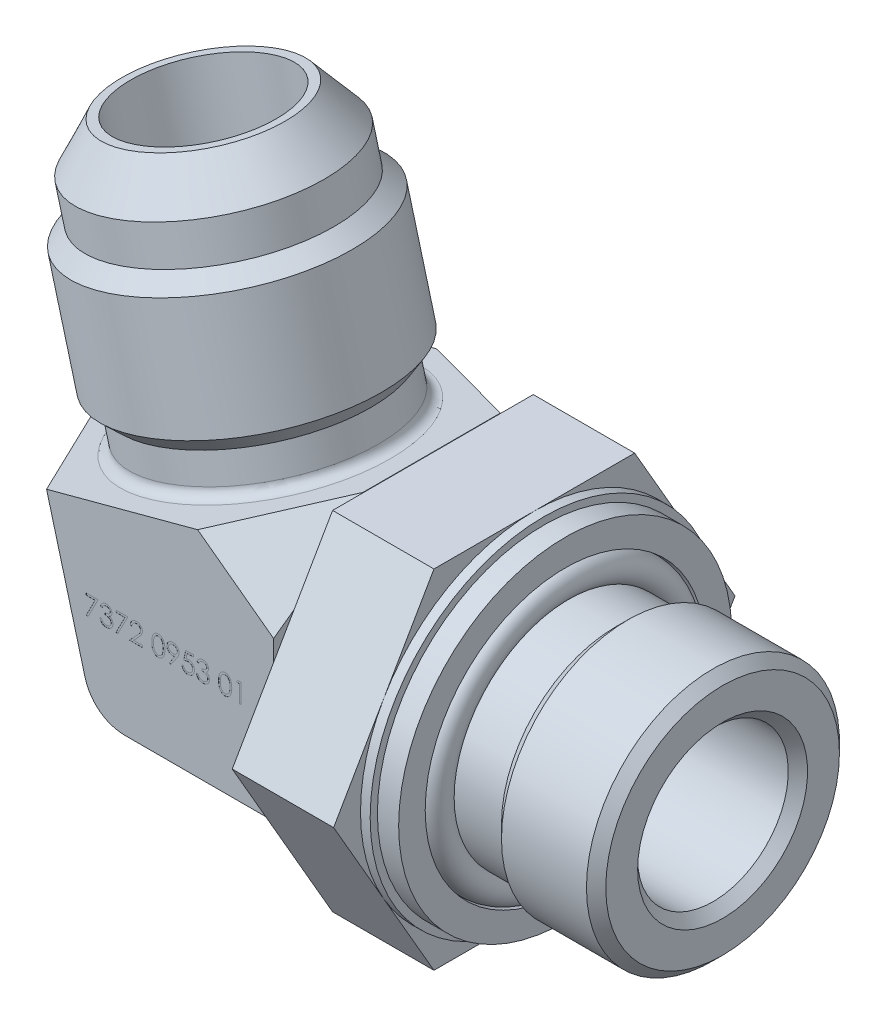
SolidWorks part; units mm, degrees
material "4140 H/T"
ref_plane "Front Plane" through (0, 0, 0) normal (0, 0, 1) x (1, 0, 0)
ref_plane "Top Plane" through (0, 0, 0) normal (0, 1, 0) x (1, 0, 0)
ref_plane "Right Plane" through (0, 0, 0) normal (1, 0, 0) x (0, 0, -1)
sketch "Sketch1" plane through (0, 0, 0) normal (0, 0, 1) x (1, 0, 0)
  line L0 (-0.372, 0.2753) -> (0.372, -0.2753)
  line L1 (0.372, -0.2753) -> (0.372, -30.7753)
  line L2 (0.372, -30.7753) -> (-23.628, -30.7753)
  line L3 (-23.628, -30.7753) -> (-29.8328, -7.6187)
  line L4 (-29.8328, -7.6187) -> (-0.372, 0.2753)
  line L5 (0, 0) -> (3.978, 0) construction
  line L6 (0, 0) -> (0, 1.2532) construction
  line L7 (-15.1024, -3.6717) -> (-11.3976, -17.4981) construction
  line L8 (0.372, -15.5253) -> (13.3109, -15.5253) construction
  dimension "D1" = 24
  dimension "D2" = 75
  dimension "D3" = 36.5
  dimension "D4" = 30.5
  dimension "D5" = 30.5
  dimension "D6" = 105
extrude "Extrude1" add sketch "Sketch1" along normal mid plane 30
chamfer "Chamfer1" distance 12 angle 30 4 edges at (-11.628, -30.7753, -15) (-11.628, -30.7753, 15) (-26.7304, -19.197, 15) (-26.7304, -19.197, -15)
fillet "Fillet1" radius 11 1 edges at (-23.628, -30.7753, 0)
chamfer "Chamfer2" distance 10 angle 30 2 edges at (0, 0, -15) (0, 0, 15)
fillet "Fillet4" radius 5 2 edges at (-20.0978, -26.1746, 10.9686) (-20.0978, -26.1746, -10.9686)
sketch "Sketch3" plane through (-0.0937, 0.3499, 0) normal (-0.2588, 0.9659, 0) x (0.9659, 0.2588, 0)
  line L0 (0, 0) -> (-30.7881, 0) construction
  line L1 (-30.7881, -3) -> (-30.7881, 3) construction
  point P0 (-15.3941, 0)
sketch "Sketch4" plane through (0, 0, 0) normal (0, 0, 1) x (1, 0, 0)
  line L0 (-14.9633, -3.6344) -> (-20.7732, 18.0487) construction
  line L1 (-0.0937, 0.3499) -> (-29.8328, -7.6187) construction
  line L2 (-29.3431, -1.7417) -> (-32.3713, 9.5596)
  line L3 (-32.3713, 9.5596) -> (-31.2753, 11.458)
  line L4 (-31.2753, 11.458) -> (-32.2811, 15.2117)
  line L5 (-32.2811, 15.2117) -> (-30.3515, 19.9877)
  line L6 (-30.3515, 19.9877) -> (-29.4338, 20.2336)
  line L7 (-29.4338, 20.2336) -> (-22.4975, -5.6532)
  line L8 (-26.4095, -6.7014) -> (-22.4975, -5.6532)
  line L9 (-29.3431, -1.7417) -> (-27.4447, -2.8377)
  line L10 (-27.4447, -2.8377) -> (-26.4095, -6.7014)
  dimension "D1" = 26.8
  dimension "D2" = 23.7
  dimension "D3" = 15.6
  dimension "D4" = 37
  dimension "D5" = 4
  dimension "D6" = 26.8
  dimension "D7" = 17.5
  dimension "D8" = 45
  dimension "D9" = 8
  dimension "D10" = 45
revolve "Revolve1" add sketch "Sketch4" angle 360 about L0
cosmetic thread "Cosmetic Thread2" parameters "D1"=12, "D2"=25
sketch "Sketch5" plane through (0, 0, 0) normal (0, 0, 1) x (1, 0, 0)
  line L0 (0.372, -15.5253) -> (26.07, -15.5253) construction
  line L2 (0.372, -0.2753) -> (0.372, -30.7753) construction
  line L3 (0.372, -2.4253) -> (14.072, -2.4253)
  line L4 (31.872, -3.4253) -> (31.872, -6.7253)
  line L5 (31.872, -6.7253) -> (30.872, -7.7253)
  line L6 (30.872, -7.7253) -> (0.372, -7.7253)
  line L7 (0.372, -2.4253) -> (0.372, -7.7253)
  line L8 (30.872, -2.4253) -> (31.872, -3.4253)
  line L9 (22.072, -2.4253) -> (20.772, -3.7253)
  line L10 (20.772, -3.7253) -> (15.372, -3.7253)
  line L11 (15.372, -3.7253) -> (14.072, -2.4253)
  line L12 (22.072, -2.4253) -> (30.872, -2.4253)
  line L13 (0.372, -23.8471) -> (0.372, -7.4575) construction
  dimension "D1" = 1
  dimension "D2" = 45
  dimension "D3" = 26.2
  dimension "D4" = 15.6
  dimension "D5" = 1
  dimension "D6" = 45
  dimension "D7" = 31.5
  dimension "D8" = 9.8
  dimension "D9" = 45
  dimension "D10" = 45
  dimension "D11" = 8
  dimension "D12" = 23.6
  dimension "D13" = 15.5253
revolve "Revolve2" add sketch "Sketch5" angle 360 about L0
cosmetic thread "Cosmetic Thread3" parameters "D2"=24
fillet "Fillet3" radius 1 2 edges at (0.372, -15.5253, 13.1) (-3.517, -0.5674, 0)
sketch "Sketch6" plane through (0, 0, 0) normal (0, 0, 1) x (1, 0, 0)
  line L0 (31.872, -15.5253) -> (-31.1059, -15.5253) construction
  line L1 (31.872, -27.6253) -> (31.872, -3.4253) construction
  line L2 (31.872, -7.7253) -> (-13.4413, -7.7253)
  line L3 (-13.4413, -7.7253) -> (-18.128, -15.5253)
  line L4 (31.872, -7.7253) -> (31.872, -15.5253)
  line L5 (30.872, -7.7253) -> (0.372, -7.7253) construction
  line L6 (31.872, -15.5253) -> (-18.128, -15.5253)
  dimension "D1" = 59
  dimension "D2" = 50
revolve "Cut-Revolve1" cut sketch "Sketch6" angle 360 about L0
sketch "Sketch7" plane through (0, 0, 0) normal (0, 0, 1) x (1, 0, 0)
  line L0 (-20.7732, 18.0487) -> (-10.6383, -19.7753) construction
  line L1 (-14.9633, -3.6344) -> (-20.7732, 18.0487) construction
  line L2 (-29.4338, 20.2336) -> (-19.7764, -15.8083)
  line L3 (-29.4338, 20.2336) -> (-22.4975, -5.6532) construction
  line L4 (-19.7764, -15.8083) -> (-11.0292, -18.3165)
  line L6 (-29.4338, 20.2336) -> (-21.8996, 22.2524)
  line L7 (-13.4478, 24.5171) -> (-30.3515, 19.9877) construction
  line L8 (-11.0292, -18.3165) -> (-21.8996, 22.2524)
  dimension "D1" = 59
  dimension "D2" = 42
revolve "Cut-Revolve2" cut sketch "Sketch7" angle 360 about L0
sketch "Sketch8" plane through (0.372, 0, 0) normal (1, 0, 0) x (0, 0, -1)
  line L1 (20.7846, -15.5253) -> (10.3923, 2.4747)
  line L2 (10.3923, 2.4747) -> (-10.3923, 2.4747)
  line L3 (-10.3923, 2.4747) -> (-20.7846, -15.5253)
  line L4 (-20.7846, -15.5253) -> (-10.3923, -33.5253)
  line L5 (-10.3923, -33.5253) -> (10.3923, -33.5253)
  line L6 (10.3923, -33.5253) -> (20.7846, -15.5253)
  circle A0 centre (0, -15.5253) radius 18 construction
  circle A1 centre (0, -15.5253) radius 7.8
  arc A2 (7.4401, -13.1833) -> (-7.4401, -13.1833) centre (0, -15.5253) ccw construction
  dimension "D1" = 36
extrude "Boss-Extrude1" add sketch "Sketch8" along normal blind 10.5 from offset 1.5
sketch "Sketch9" plane through (0, 0, 0) normal (0, 0, 1) x (1, 0, 0)
  line L0 (0.372, -15.5253) -> (34.7871, -15.5253) construction
  line L2 (12.372, -1.0253) -> (12.372, 2.4747)
  line L3 (12.372, 2.4747) -> (13.372, 2.4747)
  line L4 (13.372, 2.4747) -> (13.372, 1.7247)
  line L5 (13.372, 1.7247) -> (15.572, 1.7247)
  line L6 (15.572, 1.7247) -> (15.572, -1.0253)
  line L7 (15.572, -1.0253) -> (12.372, -1.0253)
  dimension "D1" = 36
  dimension "D2" = 34.5
  dimension "D3" = 3.2
  dimension "D4" = 1
  dimension "D5" = 29
revolve "Revolve3" add sketch "Sketch9" angle 360 about L0
sketch "Sketch10" plane through (0, 0, 0) normal (0, 0, 1) x (1, 0, 0)
  line L0 (13.372, -33.5253) -> (13.372, 2.4747) construction
  line L1 (0.372, -15.5253) -> (42.3473, -15.5253) construction
  circle A0 centre (14.872, -2.6023) radius 1.5
  dimension "D1" = 3
  dimension "D2" = 25.8459
revolve "Revolve4" add sketch "Sketch10" angle 360 about L1
sketch "Sketch11" plane through (0, 0, 15) normal (0, 0, 1) x (1, 0, 0)
  line L0 (-19.2432, -15.0744) -> (0, -15.0744) construction
  text T0 "7372 0953 01"
extrude "Cut-Extrude1" cut sketch "Sketch11" against normal blind 0.01
